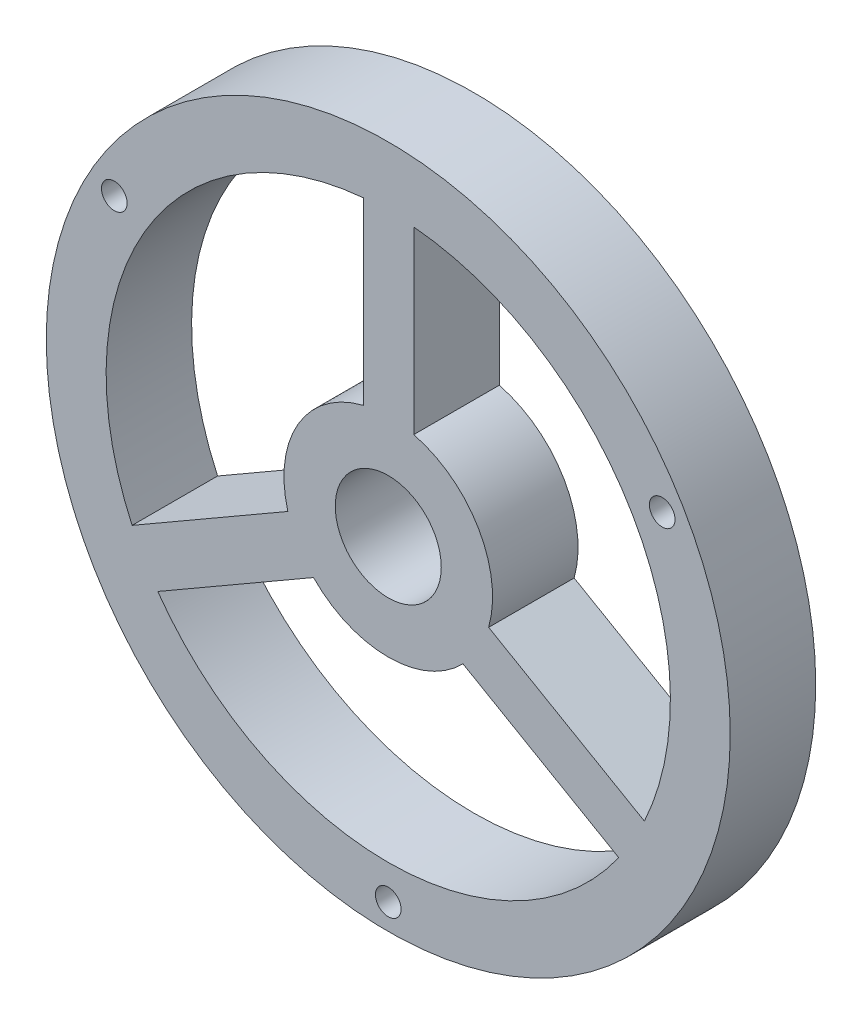
SolidWorks part; units mm, degrees
ref_plane "前视基准面" through (0, 0, 0) normal (0, 0, 1) x (1, 0, 0)
ref_plane "上视基准面" through (0, 0, 0) normal (0, 1, 0) x (1, 0, 0)
ref_plane "右视基准面" through (0, 0, 0) normal (1, 0, 0) x (0, 0, -1)
sketch "草图1" plane through (0, 0, 0) normal (0, 0, 1) x (1, 0, 0)
  line L0 (48.2965, 27.9249) -> (48.2965, 47.9249) construction
  line L1 (48.2965, 27.9249) -> (30.976, 17.9249) construction
  line L2 (48.2965, 27.9249) -> (74.2772, 12.9249) construction
  line L3 (81.0732, 9.0013) -> (81.8232, 10.3003)
  line L7 (46.8483, 66.0915) -> (46.8483, 32.6388)
  line L11 (49.7879, 66.0915) -> (49.7879, 32.6388)
  line L12 (81.0732, 9.0013) -> (80.3232, 7.7022)
  line L13 (81.8232, 10.3003) -> (52.5654, 27.1923)
  line L14 (52.5654, 27.1923) -> (51.0654, 24.5942)
  line L15 (51.0654, 24.5942) -> (80.3232, 7.7022)
  line L16 (15.5198, 9.0013) -> (14.7698, 10.3003)
  line L17 (15.5198, 9.0013) -> (16.2698, 7.7022)
  line L18 (14.7698, 10.3003) -> (43.9274, 27.1345)
  line L19 (43.9274, 27.1345) -> (45.4274, 24.5364)
  line L20 (45.4274, 24.5364) -> (16.2698, 7.7022)
  line L21 (46.8483, 32.6388) -> (49.7879, 32.6388)
  line L22 (46.8483, 66.0915) -> (49.7879, 66.0915)
  circle A1 centre (48.2965, 27.9249) radius 3.1
  circle A2 centre (48.2965, 27.9249) radius 6.1
  circle A3 centre (48.2965, 27.9249) radius 20
  circle A4 centre (48.2965, 27.9249) radius 16.5
  dimension "D1" = 3
  dimension "D2" = 3.5
extrude "凸台-拉伸2" add sketch "草图1" along normal blind 5 contours A4 L7 A3 L18 | A4 L13 A3 L11 | A4 L20 A3 L15 | A4 L18 A3 L20 | L18 A4 L20 A2 | L7 A2 L18 L19 L20 L15 L14 L13 L11 L21 A1 | L18 A2 L20 L19 | L15 A2 L13 L14 | L11 A2 L7 L21 | L11 A4 L7 A2 | L15 A4 L13 A2 | A4 L15 A3 L13 | A4 L11 A3 L7
sketch "草图2" plane through (0, 0, 5) normal (0, 0, 1) x (1, 0, 0)
  line L0 (48.2965, 27.9249) -> (32.275, 37.1749)
  line L1 (48.2965, 27.9249) -> (64.3179, 37.1749)
  line L2 (48.2965, 27.9249) -> (48.2965, 9.4249)
  circle A0 centre (32.275, 37.1749) radius 0.75
  circle A1 centre (64.3179, 37.1749) radius 0.75
  circle A2 centre (48.2965, 9.4249) radius 0.75
extrude "切除-拉伸1" cut sketch "草图2" against normal blind 5
